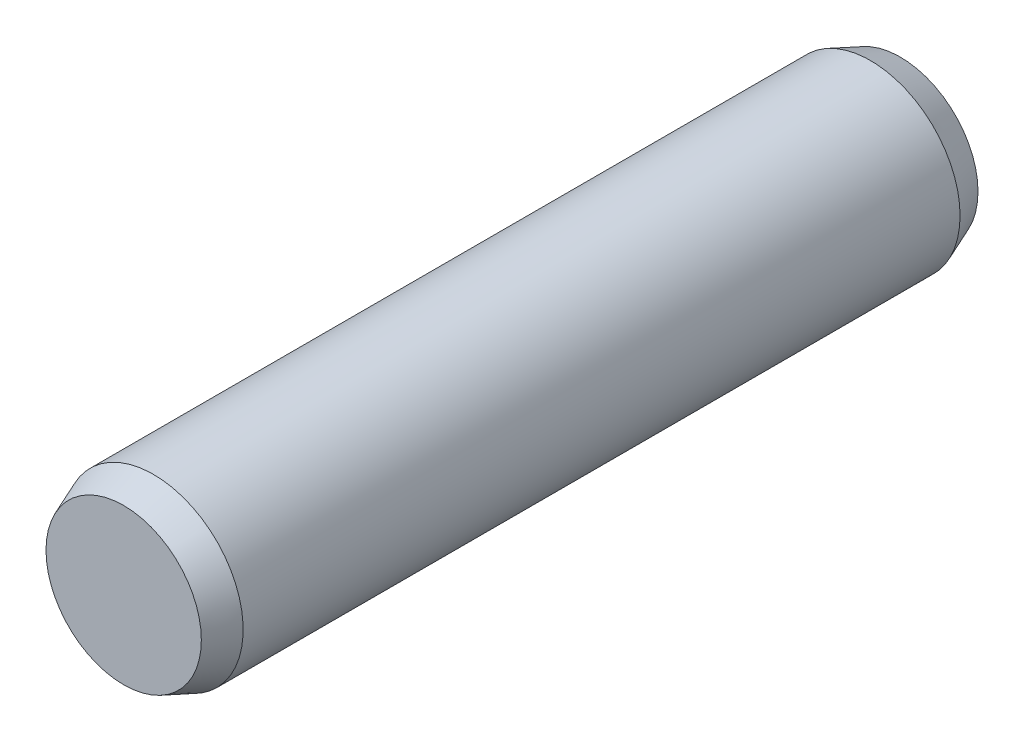
SolidWorks part; units mm, degrees
ref_plane "Front Plane" through (0, 0, 0) normal (0, 0, 1) x (1, 0, 0)
ref_plane "Top Plane" through (0, 0, 0) normal (0, 1, 0) x (1, 0, 0)
ref_plane "Right Plane" through (0, 0, 0) normal (1, 0, 0) x (0, 0, -1)
sketch "Sketch1" plane through (0, 0, 0) normal (0, 0, 1) x (1, 0, 0)
  circle A0 centre (0, 0) radius 1.5
  dimension "D1" = 3
extrude "Boss-Extrude1" add sketch "Sketch1" along normal mid plane 13
chamfer "Chamfer1" distance 0.5 distance2 0.2 1 edges at (1.5, 0, 6.5)
chamfer "Chamfer2" distance 0.2 distance2 0.5 1 edges at (1.5, 0, -6.5)
